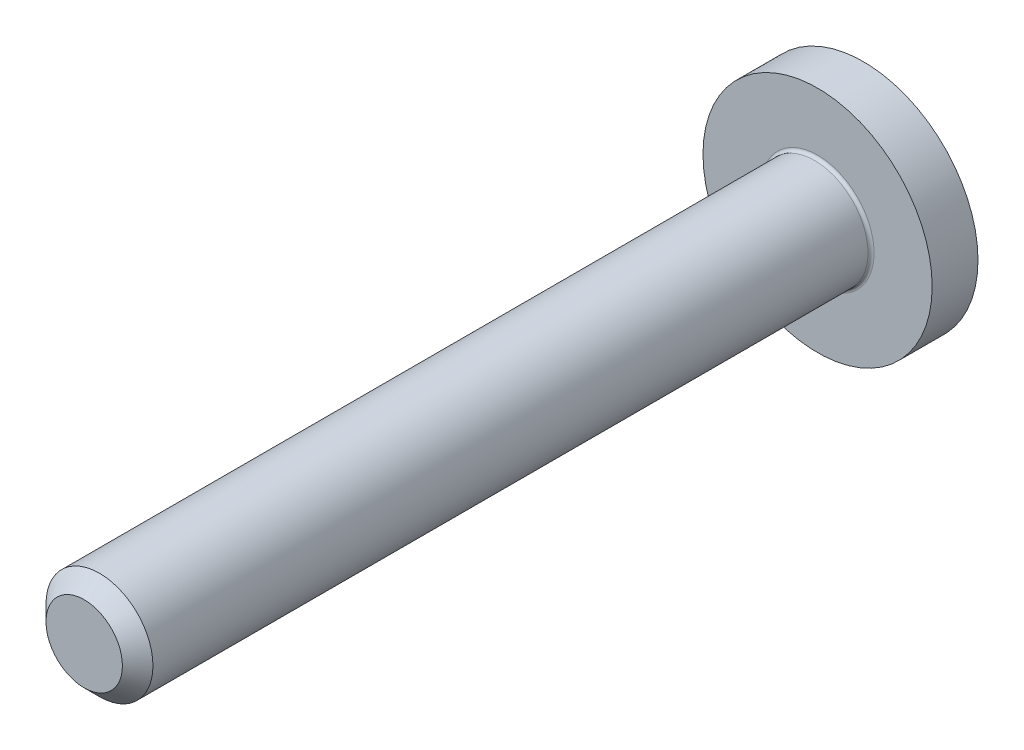
SolidWorks part; units mm, degrees
ref_plane "Front Plane" through (0, 0, 0) normal (0, 0, 1) x (1, 0, 0)
ref_plane "Top Plane" through (0, 0, 0) normal (0, 1, 0) x (1, 0, 0)
ref_plane "Right Plane" through (0, 0, 0) normal (1, 0, 0) x (0, 0, -1)
sketch "Sketch1" plane through (0, 0, 0) normal (0, 0, 1) x (1, 0, 0)
  circle A0 centre (0, 0) radius 3.5
  dimension "D1" = 7
extrude "Boss-Extrude1" add sketch "Sketch1" along normal blind 48
sketch "Sketch2" plane through (0, 0, 0) normal (0, 0, -1) x (-1, 0, 0)
  circle A0 centre (0, 0) radius 7.5
  dimension "D1" = 15
extrude "Boss-Extrude2" add sketch "Sketch2" along normal blind 3
chamfer "Chamfer1" distance 1 angle 45 1 edges at (3.5, 0, 48)
fillet "Fillet1" radius 0.2 1 edges at (3.5, 0, 0)
